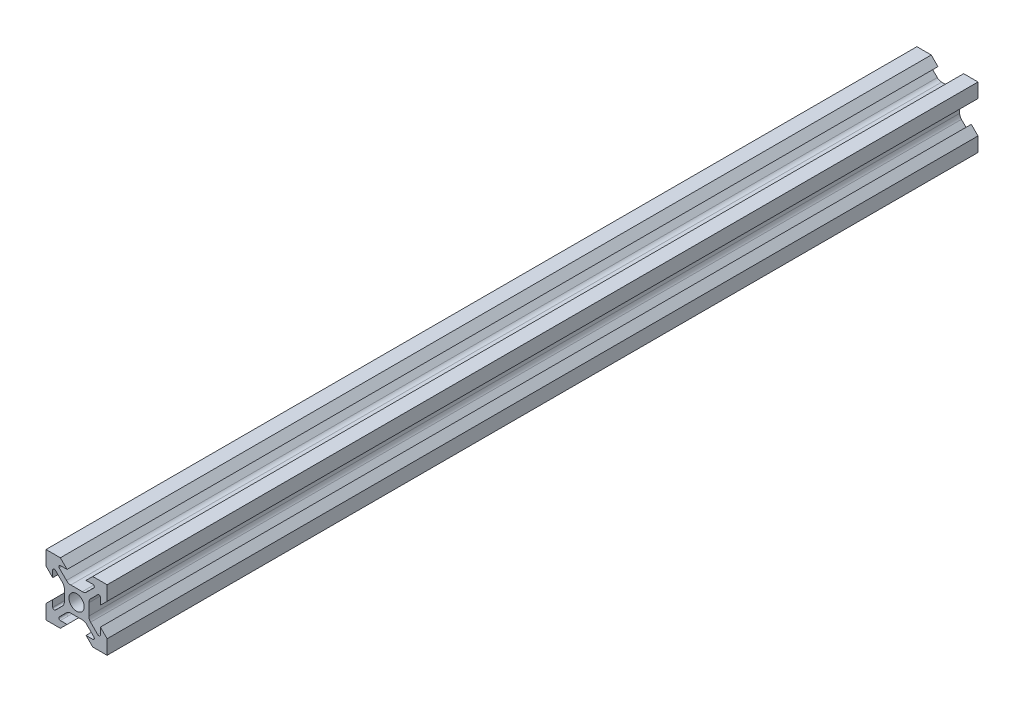
SolidWorks part; units mm, degrees
ref_plane "Front Plane" through (0, 0, 0) normal (0, 0, 1) x (1, 0, 0)
ref_plane "Top Plane" through (0, 0, 0) normal (0, 1, 0) x (1, 0, 0)
ref_plane "Right Plane" through (0, 0, 0) normal (1, 0, 0) x (0, 0, -1)
sketch "Sketch1" plane through (0, 0, 0) normal (0, 0, 1) x (1, 0, 0)
  line L0 (0, 0) -> (0, 10) construction
  line L1 (0, 10) -> (-10, 10) construction
  line L2 (-10, 10) -> (-10, 0) construction
  line L3 (-10, 0) -> (0, 0) construction
  line L4 (0, 0) -> (-10, 10) construction
  line L5 (-10, 10) -> (-10, 5.3)
  line L6 (-10, 5.3) -> (-7.8, 3.1)
  line L7 (-7.8, 3.1) -> (-7.8, 5.3201)
  line L8 (-6.9464, 5.6737) -> (-4.5858, 3.313)
  line L9 (-4, 1.8988) -> (-4, 0)
  line L10 (-10, 10) -> (-5.3, 10)
  line L11 (-5.3, 10) -> (-3.1, 7.8)
  line L12 (-3.1, 7.8) -> (-5.3201, 7.8)
  line L13 (-5.6737, 6.9464) -> (-3.313, 4.5858)
  line L14 (-1.8988, 4) -> (0, 4)
  line L15 (10, 10) -> (5.3, 10)
  line L16 (5.3, 10) -> (3.1, 7.8)
  line L17 (3.1, 7.8) -> (5.3201, 7.8)
  line L18 (5.6737, 6.9464) -> (3.313, 4.5858)
  line L19 (1.8988, 4) -> (0, 4)
  line L20 (10, 10) -> (10, 5.3)
  line L21 (10, 5.3) -> (7.8, 3.1)
  line L22 (7.8, 3.1) -> (7.8, 5.3201)
  line L23 (6.9464, 5.6737) -> (4.5858, 3.313)
  line L24 (4, 1.8988) -> (4, 0)
  line L25 (0, 0) -> (10, 0) construction
  line L26 (10, 0) -> (10, 10) construction
  line L27 (10, 10) -> (0, 10) construction
  line L28 (0, 10) -> (0, 0) construction
  line L29 (0, 0) -> (10, 10) construction
  line L30 (10, -10) -> (10, -5.3)
  line L31 (10, -5.3) -> (7.8, -3.1)
  line L32 (7.8, -3.1) -> (7.8, -5.3201)
  line L33 (6.9464, -5.6737) -> (4.5858, -3.313)
  line L34 (4, -1.8988) -> (4, 0)
  line L35 (10, -10) -> (5.3, -10)
  line L36 (5.3, -10) -> (3.1, -7.8)
  line L37 (3.1, -7.8) -> (5.3201, -7.8)
  line L38 (5.6737, -6.9464) -> (3.313, -4.5858)
  line L39 (1.8988, -4) -> (0, -4)
  line L40 (0, 0) -> (0, -10) construction
  line L41 (0, -10) -> (10, -10) construction
  line L42 (10, -10) -> (10, 0) construction
  line L43 (10, 0) -> (0, 0) construction
  line L44 (0, 0) -> (10, -10) construction
  line L45 (-10, -10) -> (-5.3, -10)
  line L46 (-5.3, -10) -> (-3.1, -7.8)
  line L47 (-3.1, -7.8) -> (-5.3201, -7.8)
  line L48 (-5.6737, -6.9464) -> (-3.313, -4.5858)
  line L49 (-1.8988, -4) -> (0, -4)
  line L50 (-10, -10) -> (-10, -5.3)
  line L51 (-10, -5.3) -> (-7.8, -3.1)
  line L52 (-7.8, -3.1) -> (-7.8, -5.3201)
  line L53 (-6.9464, -5.6737) -> (-4.5858, -3.313)
  line L54 (-4, -1.8988) -> (-4, 0)
  line L55 (0, 0) -> (-10, 0) construction
  line L56 (-10, 0) -> (-10, -10) construction
  line L57 (-10, -10) -> (0, -10) construction
  line L58 (0, -10) -> (0, 0) construction
  line L59 (0, 0) -> (-10, -10) construction
  circle A0 centre (0, 0) radius 2.5
  arc A1 (-7.8, 5.3201) -> (-6.9464, 5.6737) centre (-7.3, 5.3201) cw
  arc A2 (-4.5858, 3.313) -> (-4, 1.8988) centre (-6, 1.8988) cw
  arc A3 (-5.3201, 7.8) -> (-5.6737, 6.9464) centre (-5.3201, 7.3) ccw
  arc A4 (-3.313, 4.5858) -> (-1.8988, 4) centre (-1.8988, 6) ccw
  arc A5 (5.3201, 7.8) -> (5.6737, 6.9464) centre (5.3201, 7.3) cw
  arc A6 (3.313, 4.5858) -> (1.8988, 4) centre (1.8988, 6) cw
  arc A7 (7.8, 5.3201) -> (6.9464, 5.6737) centre (7.3, 5.3201) ccw
  arc A8 (4.5858, 3.313) -> (4, 1.8988) centre (6, 1.8988) ccw
  arc A9 (7.8, -5.3201) -> (6.9464, -5.6737) centre (7.3, -5.3201) cw
  arc A10 (4.5858, -3.313) -> (4, -1.8988) centre (6, -1.8988) cw
  arc A11 (5.3201, -7.8) -> (5.6737, -6.9464) centre (5.3201, -7.3) ccw
  arc A12 (3.313, -4.5858) -> (1.8988, -4) centre (1.8988, -6) ccw
  arc A13 (-5.3201, -7.8) -> (-5.6737, -6.9464) centre (-5.3201, -7.3) cw
  arc A14 (-3.313, -4.5858) -> (-1.8988, -4) centre (-1.8988, -6) cw
  arc A15 (-7.8, -5.3201) -> (-6.9464, -5.6737) centre (-7.3, -5.3201) ccw
  arc A16 (-4.5858, -3.313) -> (-4, -1.8988) centre (-6, -1.8988) ccw
  dimension "D1" = 5
  dimension "D5" = 2
  dimension "D7" = 0.5
  dimension "D2" = 10
  dimension "D3" = 5.3
  dimension "D4" = 6
  dimension "D6" = 0.9
  dimension "D8" = 3.1
  dimension "D10" = 20
  dimension "D9" = 4
extrude "Boss-Extrude1" add sketch "Sketch1" along normal blind 285
